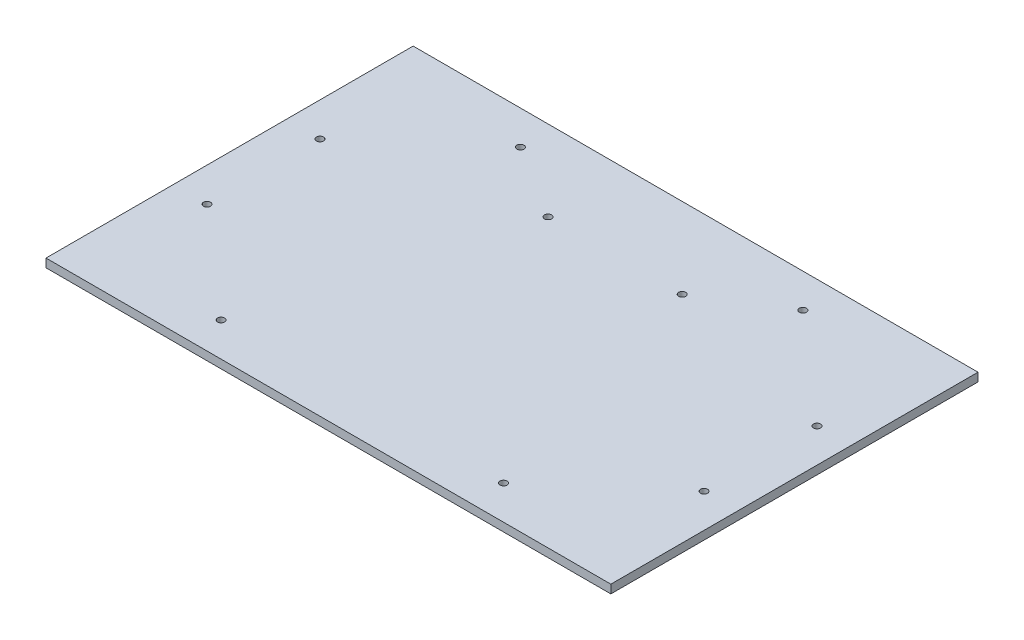
SolidWorks part; units mm, degrees
ref_plane "Plan de face" through (0, 0, 0) normal (0, 0, 1) x (1, 0, 0)
ref_plane "Plan de dessus" through (0, 0, 0) normal (0, 1, 0) x (1, 0, 0)
ref_plane "Plan de droite" through (0, 0, 0) normal (1, 0, 0) x (0, 0, -1)
sketch "Esquisse1" plane through (0, 0, 0) normal (0, 1, 0) x (1, 0, 0)
  line L1 (-200, -130) -> (200, -130)
  line L2 (-200, -130) -> (-200, 130)
  line L3 (-200, 130) -> (200, 130)
  line L4 (200, -130) -> (200, 130)
  line L5 (-200, -130) -> (200, 130) construction
  line L6 (-200, 130) -> (200, -130) construction
  point P0 (0, 0)
  dimension "D1" = 400
  dimension "D2" = 260
extrude "Boss.-Extru.1" add sketch "Esquisse1" along normal blind 6
sketch "Esquisse2" plane through (0, 0, 0) normal (0, -1, 0) x (1, 0, 0)
  line L0 (-200, -130) -> (-200, 130) construction
  line L1 (-176, -106) -> (176, -106) construction
  line L2 (-176, -106) -> (-176, 106) construction
  line L3 (-176, 106) -> (176, 106) construction
  line L4 (176, -106) -> (176, 106) construction
  line L5 (-176, -106) -> (176, 106) construction
  line L6 (-176, 106) -> (176, -106) construction
  line L7 (-200, 130) -> (200, 130) construction
  line L8 (0, 130) -> (0, -130) construction
  line L9 (200, -130) -> (-200, -130) construction
  line L10 (-200, 0) -> (200, 0) construction
  line L11 (200, 130) -> (200, -130) construction
  circle A0 centre (-100, 106) radius 2.5
  circle A1 centre (100, 106) radius 2.5
  circle A2 centre (176, 40) radius 2.5
  circle A3 centre (176, -40) radius 2.5
  circle A4 centre (100, -106) radius 2.5
  circle A5 centre (-100, -106) radius 2.5
  circle A6 centre (-176, -40) radius 2.5
  circle A7 centre (-176, 40) radius 2.5
  point P0 (0, 0)
  dimension "D3" = 5
  dimension "D1" = 24
  dimension "D2" = 24
  dimension "D4" = 200
  dimension "D5" = 80
extrude "Enlèv. mat.-Extru.1" cut sketch "Esquisse2" against normal through all
chamfer "Chanfrein1" [suppressed] distance 2 angle 45
sketch "Esquisse3" plane through (0, 0, 0) normal (0, -1, 0) x (1, 0, 0)
  line L0 (47.5, -73) -> (-47.5, -73) construction
  line L1 (200, -130) -> (-200, -130) construction
  circle A0 centre (47.5, -73) radius 2.5
  circle A1 centre (-47.5, -73) radius 2.5
  point P4 (0, -73)
  dimension "D3" = 5
  dimension "D1" = 57
  dimension "D2" = 95
extrude "Enlèv. mat.-Extru.2" cut sketch "Esquisse3" against normal through all
chamfer "Chanfrein2" distance 2 angle 45 2 edges at (-47.5, 0, -75.5) (47.5, 0, -75.5)
